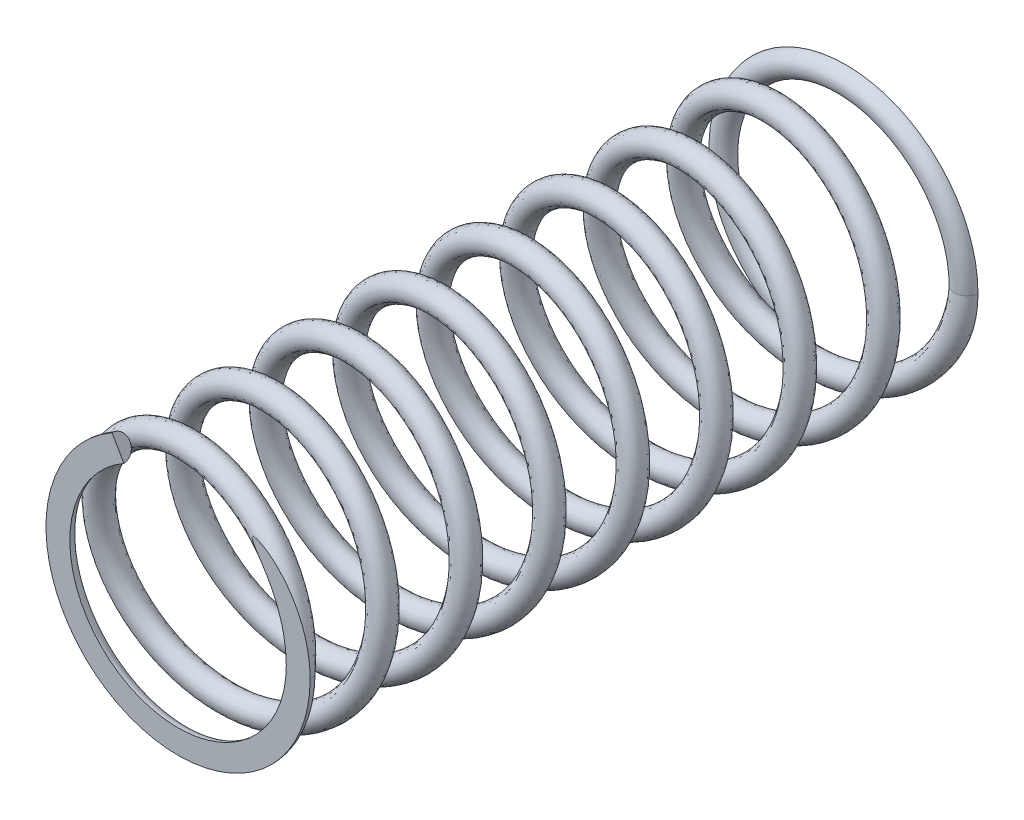
SolidWorks part; units mm, degrees
material "Alloy Steel"
ref_plane "X-Y Datum" through (0, 0, 0) normal (0, 0, 1) x (1, 0, 0)
ref_plane "X-Z Datum" through (0, 0, 0) normal (0, 1, 0) x (1, 0, 0)
ref_plane "Y-Z Datum" through (0, 0, 0) normal (1, 0, 0) x (0, 0, -1)
sketch "Sketch2" plane through (0, 0, 0) normal (0, 0, 1) x (1, 0, 0)
  circle A0 centre (0, 0) radius 18.15 construction
  circle A1 centre (0, 0) radius 20.15
  dimension "D1" = 36.3
  dimension "D2" = 2
curve "Helix/Spiral1" pitch 13.9998 height 111.9988 turns 8
ref_plane "Cap Plane" through (0, 0, 111.9988) normal (0, 0, 1) x (1, 0, 0)
sketch "Sketch10" plane through (0, 0, 111.9988) normal (0, 0, 1) x (1, 0, 0)
  circle A3 centre (0, 0) radius 20.15 construction
  circle A4 centre (0, 0) radius 20.15 construction
  arc A5 (20.15, 0) -> (-10.075, 17.4504) centre (0, 0) cw
  dimension "D1" = 120
sweep "Sweep1" add path "Helix/Spiral1" circular profile diameter 4 parameters "D3"=4
sweep "Sweep2" add path "Sketch10" circular profile diameter 4 parameters "D3"=4
sketch "Sketch41" plane through (0, 0, 111.9988) normal (0, 0, 1) x (1, 0, 0)
  circle A0 centre (0, 0) radius 25
  dimension "D1" = 50
extrude "Cut-Extrude1" cut sketch "Sketch41" along normal through all
sketch "Sketch42" plane through (0, 0, 0) normal (0, 0, 1) x (1, 0, 0)
  circle A0 centre (0, 0) radius 20.15 construction
  circle A1 centre (0, 0) radius 20.15 construction
  arc A2 (20.15, 0) -> (-10.075, -17.4504) centre (0, 0) ccw
  dimension "D1" = 120
sweep "Sweep3" add path "Sketch42" circular profile diameter 4 parameters "D3"=4
sketch "Sketch55" plane through (0, 0, 0) normal (0, 0, 1) x (1, 0, 0)
  circle A0 centre (0, 0) radius 25 construction
  circle A1 centre (0, 0) radius 25
extrude "Cut-Extrude2" cut sketch "Sketch55" against normal through all
